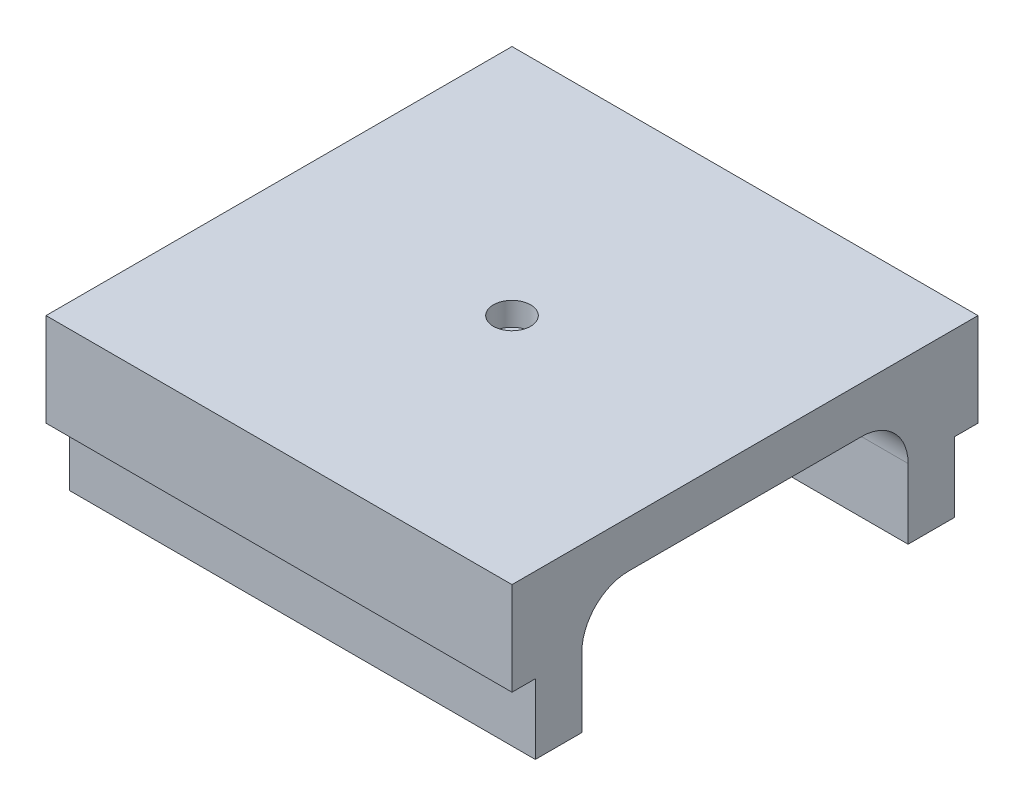
SolidWorks part; units mm, degrees
ref_plane "Front Plane" through (0, 0, 0) normal (0, 0, 1) x (1, 0, 0)
ref_plane "Top Plane" through (0, 0, 0) normal (0, 1, 0) x (1, 0, 0)
ref_plane "Right Plane" through (0, 0, 0) normal (1, 0, 0) x (0, 0, -1)
sketch "Sketch1" plane through (0, 0, 0) normal (0, 1, 0) x (1, 0, 0)
  line L1 (50, -50) -> (-50, -50)
  line L2 (50, -50) -> (50, 50)
  line L3 (50, 50) -> (-50, 50)
  line L4 (-50, -50) -> (-50, 50)
  line L5 (50, -50) -> (-50, 50) construction
  line L6 (50, 50) -> (-50, -50) construction
  circle A0 centre (0, 0) radius 3.5846
  dimension "D1" = 100
  dimension "D2" = 100
extrude "Boss-Extrude1" add sketch "Sketch1" along normal blind 20 contours L4 L1 L2 L3 A0
sketch "Sketch3" plane through (0, 20, 0) normal (0, 1, 0) x (1, 0, 0)
  circle A0 centre (0, 0) radius 4
extrude "Cut-Extrude1" cut sketch "Sketch3" against normal blind 5
sketch "Sketch4" plane through (0, 0, 0) normal (0, -1, 0) x (1, 0, 0)
  line L0 (50, -35) -> (-40, -35)
  line L1 (50, 50) -> (50, -50) construction
  line L3 (-40, 35) -> (50, 35)
  line L5 (50, 50) -> (-50, 50) construction
  line L6 (50, -35) -> (50, -45)
  line L7 (-40, -45) -> (50, -45)
  line L10 (50, 45) -> (50, 35)
  line L11 (0, 0) -> (-73.7994, 0) construction
  line L13 (-40, 45) -> (50, 45)
  line L16 (-40, 45) -> (-50, 45)
  line L17 (-50, 50) -> (-50, -50) construction
  line L18 (-40, 35) -> (-50, 35)
  line L19 (-50, 35) -> (-50, 45)
  line L20 (-40, -35) -> (-50, -35)
  line L21 (-40, -45) -> (-50, -45)
  line L22 (-50, -45) -> (-50, -35)
  point P24 (-45, 0)
  dimension "D1" = 90
  dimension "D2" = 15
extrude "Boss-Extrude2" add sketch "Sketch4" along normal blind 15
sketch "Sketch5" plane through (0, 0, 0) normal (0, -1, 0) x (1, 0, 0)
  line L0 (-50, 35) -> (-50, -35)
  line L1 (-50, -35) -> (50, -35)
  line L2 (50, -35) -> (50, 35)
  line L3 (50, 35) -> (-50, 35)
extrude "Cut-Extrude2" cut sketch "Sketch5" against normal blind 10
fillet "Fillet2" radius 10 1 edges at (0, 10, -35)
fillet "Fillet3" radius 10 1 edges at (0, 10, 35)
sketch "Sketch6" plane through (0, 10, 0) normal (0, -1, 0) x (1, 0, 0)
  line L0 (-35, 25) -> (-35, -25)
  line L1 (50, 25) -> (-50, 25) construction
  line L2 (-50, -25) -> (50, -25) construction
  line L3 (-35, -25) -> (-30, -25)
  line L4 (-30, -25) -> (-30, 25)
  line L5 (-30, 25) -> (-35, 25)
  line L6 (-50, 25) -> (-50, -25) construction
  dimension "D1" = 15
  dimension "D2" = 5
extrude "Boss-Extrude3" add sketch "Sketch6" along normal blind 8
